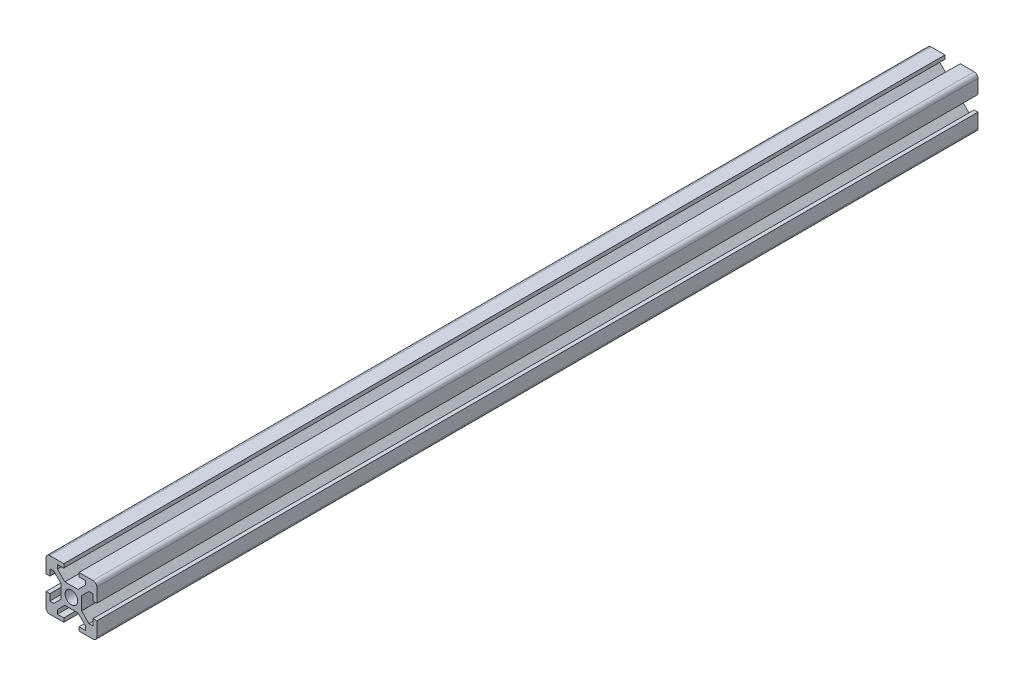
SolidWorks part; units mm, degrees
ref_plane "Front Plane" through (0, 0, 0) normal (0, 0, 1) x (1, 0, 0)
ref_plane "Top Plane" through (0, 0, 0) normal (0, 1, 0) x (1, 0, 0)
ref_plane "Right Plane" through (0, 0, 0) normal (1, 0, 0) x (0, 0, -1)
sketch "Sketch1" plane through (0, 0, 0) normal (0, 0, 1) x (1, 0, 0)
  line L0 (-2.5858, 4) -> (-5.5, 6.9142)
  line L1 (-8.5, -10) -> (-3, -10)
  line L2 (-10, -8.5) -> (-10, -3)
  line L3 (-8.5, 10) -> (-3, 10)
  line L4 (10, -8.5) -> (10, -3)
  line L5 (-10, -10) -> (10, 10) construction
  line L6 (-10, 10) -> (10, -10) construction
  line L7 (-2.5858, 4) -> (2.5858, 4)
  line L8 (-4, 2.5858) -> (-4, -2.5858)
  line L9 (-2.5858, -4) -> (2.5858, -4)
  line L10 (4, 2.5858) -> (4, -2.5858)
  line L13 (-5.5, 6.9142) -> (-5.5, 8.5)
  line L14 (-5.5, 8.5) -> (-3, 8.5)
  line L15 (-3, 8.5) -> (-3, 10)
  line L16 (-4, 2.5858) -> (-6.9142, 5.5)
  line L17 (-8.5, 5.5) -> (-8.5, 3)
  line L18 (-6.9142, 5.5) -> (-8.5, 5.5)
  line L19 (-8.5, 3) -> (-10, 3)
  line L20 (8.5, 5.5) -> (8.5, 3)
  line L21 (8.5, 3) -> (10, 3)
  line L22 (4, 2.5858) -> (6.9142, 5.5)
  line L23 (6.9142, 5.5) -> (8.5, 5.5)
  line L24 (2.5858, 4) -> (5.5, 6.9142)
  line L25 (5.5, 6.9142) -> (5.5, 8.5)
  line L26 (5.5, 8.5) -> (3, 8.5)
  line L27 (3, 8.5) -> (3, 10)
  line L28 (5.5, -8.5) -> (3, -8.5)
  line L29 (3, -8.5) -> (3, -10)
  line L30 (2.5858, -4) -> (5.5, -6.9142)
  line L31 (5.5, -6.9142) -> (5.5, -8.5)
  line L32 (4, -2.5858) -> (6.9142, -5.5)
  line L33 (6.9142, -5.5) -> (8.5, -5.5)
  line L34 (8.5, -5.5) -> (8.5, -3)
  line L35 (8.5, -3) -> (10, -3)
  line L36 (-8.5, -5.5) -> (-8.5, -3)
  line L37 (-8.5, -3) -> (-10, -3)
  line L38 (-4, -2.5858) -> (-6.9142, -5.5)
  line L39 (-6.9142, -5.5) -> (-8.5, -5.5)
  line L40 (-2.5858, -4) -> (-5.5, -6.9142)
  line L41 (-5.5, -6.9142) -> (-5.5, -8.5)
  line L42 (-5.5, -8.5) -> (-3, -8.5)
  line L43 (-3, -8.5) -> (-3, -10)
  line L44 (3, 10) -> (8.5, 10)
  line L45 (10, 3) -> (10, 8.5)
  line L46 (3, -10) -> (8.5, -10)
  line L47 (-10, 3) -> (-10, 8.5)
  circle A0 centre (0, 0) radius 2.5
  arc A1 (10, 8.5) -> (8.5, 10) centre (8.5, 8.5) ccw
  arc A2 (10, -8.5) -> (8.5, -10) centre (8.5, -8.5) cw
  arc A3 (-8.5, -10) -> (-10, -8.5) centre (-8.5, -8.5) cw
  arc A4 (-10, 8.5) -> (-8.5, 10) centre (-8.5, 8.5) cw
  point P0 (0, 0)
  point P6 (0, 0)
  point P56 (0, 0)
  dimension "D3" = 5
  dimension "D9" = 1.5
  dimension "D1" = 20
  dimension "D2" = 8
  dimension "D4" = 7
  dimension "D5" = 1.5
  dimension "D6" = 4.5
  dimension "D7" = 1
  dimension "D8" = 4
extrude "Boss-Extrude1" add sketch "Sketch1" along normal blind 347
